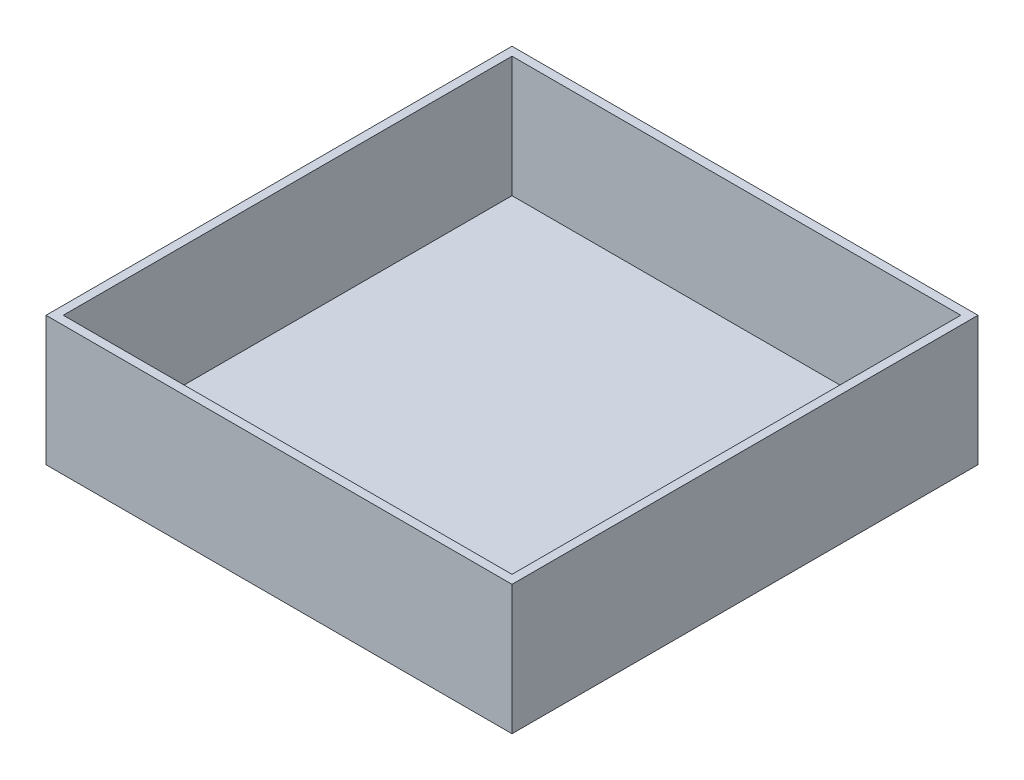
SolidWorks part; units mm, degrees
ref_plane "Front Plane" through (0, 0, 0) normal (0, 0, 1) x (1, 0, 0)
ref_plane "Top Plane" through (0, 0, 0) normal (0, 1, 0) x (1, 0, 0)
ref_plane "Right Plane" through (0, 0, 0) normal (1, 0, 0) x (0, 0, -1)
sketch "Sketch1" plane through (0, 0, 0) normal (0, 1, 0) x (1, 0, 0)
  line L2 (0, 0) -> (8229.6, 0)
  line L3 (0, 0) -> (0, 8229.6)
  line L4 (0, 8229.6) -> (8229.6, 8229.6)
  line L5 (8229.6, 0) -> (8229.6, 8229.6)
  dimension "D1" = 8229.6
  dimension "D2" = 8229.6
extrude "Extrude2" add sketch "Sketch1" along normal blind 2133.6
sketch "Sketch3" plane through (0, 2133.6, 0) normal (0, 1, 0) x (1, 0, 0)
  line L14 (8077.2, 152.4) -> (8077.2, 8077.2)
  line L15 (152.4, 152.4) -> (8077.2, 152.4)
  line L16 (152.4, 8077.2) -> (152.4, 152.4)
  line L17 (8077.2, 8077.2) -> (152.4, 8077.2)
  line L18 (8077.2, 152.4) -> (8077.2, 8077.2)
  line L19 (152.4, 152.4) -> (8077.2, 152.4)
  line L20 (152.4, 8077.2) -> (152.4, 152.4)
  line L21 (8077.2, 8077.2) -> (152.4, 8077.2)
  dimension "D1" = 152.4
extrude "Extrude3" cut sketch "Sketch3" against normal through all
sketch "Sketch4" plane through (0, 0, 0) normal (0, -1, 0) x (1, 0, 0)
  line L1 (0, 0) -> (8229.6, 0)
  line L2 (0, 0) -> (0, -8229.6)
  line L3 (0, -8229.6) -> (8229.6, -8229.6)
  line L4 (8229.6, 0) -> (8229.6, -8229.6)
  line L5 (8077.2, -8077.2) -> (152.4, -8077.2)
  line L6 (8077.2, -8077.2) -> (8077.2, -152.4)
  line L7 (8077.2, -152.4) -> (152.4, -152.4)
  line L8 (152.4, -8077.2) -> (152.4, -152.4)
extrude "Extrude4" add sketch "Sketch4" along normal blind 152.4
sketch "Sketch5" plane through (0, 0, 0) normal (0, 1, 0) x (1, 0, 0)
  line L1 (0, 0) -> (8229.6, 0)
  line L2 (0, 0) -> (0, 8229.6)
  line L3 (0, 8229.6) -> (8229.6, 8229.6)
  line L4 (8229.6, 0) -> (8229.6, 8229.6)
  dimension "D1" = 8229.6
  dimension "D2" = 8229.6
sketch "Sketch6" plane through (0, 0, -152.4) normal (0, 0, -1) x (-1, 0, 0)
  line L0 (-152.4, -152.4) -> (-152.4, 2133.6) construction
  line L1 (-8077.2, -152.4) -> (-152.4, -152.4)
  line L2 (-8077.2, -152.4) -> (-8077.2, 0)
  line L3 (-8077.2, 0) -> (-152.4, 0)
  line L4 (-152.4, -152.4) -> (-152.4, 0)
extrude "Extrude5" add sketch "Sketch6" along normal up to surface (7924.8 mm away) up to face at (4114.8, 990.6, -8077.2)
sketch "Sketch8" plane through (0, 0, -152.4) normal (0, 0, -1) x (-1, 0, 0)
  line L0 (-8077.2, 0) -> (-4572, 0)
  line L1 (-3657.6, 0) -> (-152.4, 0)
  line L2 (-4572, 0) -> (-3657.6, 0)
  line L4 (-4572, 1828.8) -> (-3657.6, 1828.8)
  line L5 (-3657.6, 0) -> (-3657.6, 1828.8)
  line L9 (-4572, 0) -> (-4572, 1828.8)
  dimension "D1" = 1828.8
